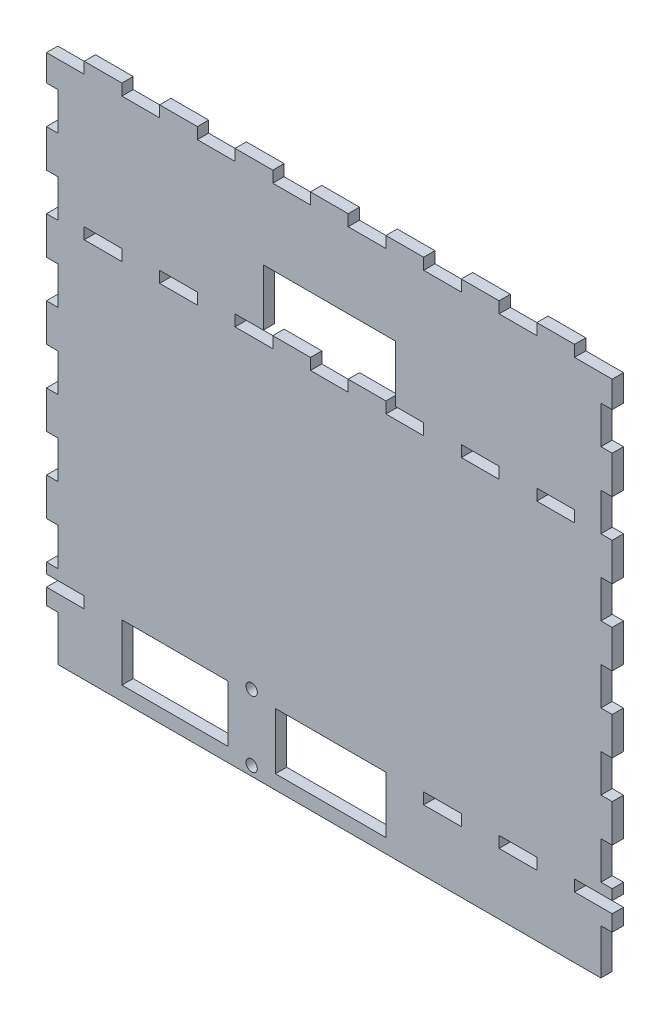
SolidWorks part; units mm, degrees
ref_plane "Alzado" through (0, 0, 0) normal (0, 0, 1) x (1, 0, 0)
ref_plane "Planta" through (0, 0, 0) normal (0, 1, 0) x (1, 0, 0)
ref_plane "Vista lateral" through (0, 0, 0) normal (1, 0, 0) x (0, 0, -1)
sketch "Croquis1" plane through (0, 0, 0) normal (0, 0, 1) x (1, 0, 0)
  line L0 (-45, 72.5) -> (-45, 69.5)
  line L1 (-72, -69.5) -> (72, -69.5)
  line L2 (-72, -69.5) -> (-72, 69.5)
  line L3 (-72, 69.5) -> (72, 69.5)
  line L4 (72, -69.5) -> (72, 69.5)
  line L5 (-72, -69.5) -> (72, 69.5) construction
  line L6 (-72, 69.5) -> (72, -69.5) construction
  line L7 (-65, 72.5) -> (-55, 72.5)
  line L8 (-65, 72.5) -> (-65, 69.5)
  line L9 (-65, 69.5) -> (-55, 69.5)
  line L10 (-55, 72.5) -> (-55, 69.5)
  line L11 (-45, 72.5) -> (-35, 72.5)
  line L12 (-35, 72.5) -> (-35, 69.5)
  line L13 (-45, 69.5) -> (-35, 69.5)
  line L14 (-25, 72.5) -> (-25, 69.5)
  line L15 (-25, 72.5) -> (-15, 72.5)
  line L16 (-15, 72.5) -> (-15, 69.5)
  line L17 (-25, 69.5) -> (-15, 69.5)
  line L18 (-5, 72.5) -> (-5, 69.5)
  line L19 (-5, 72.5) -> (5, 72.5)
  line L20 (5, 72.5) -> (5, 69.5)
  line L21 (-5, 69.5) -> (5, 69.5)
  line L22 (15, 72.5) -> (15, 69.5)
  line L23 (15, 72.5) -> (25, 72.5)
  line L24 (25, 72.5) -> (25, 69.5)
  line L25 (15, 69.5) -> (25, 69.5)
  line L26 (35, 72.5) -> (35, 69.5)
  line L27 (35, 72.5) -> (45, 72.5)
  line L28 (45, 72.5) -> (45, 69.5)
  line L29 (35, 69.5) -> (45, 69.5)
  line L30 (55, 72.5) -> (55, 69.5)
  line L31 (55, 72.5) -> (65, 72.5)
  line L32 (65, 72.5) -> (65, 69.5)
  line L33 (55, 69.5) -> (65, 69.5)
  line L58 (0, 0) -> (0, 41.2276) construction
  line L84 (-75, -50.25) -> (-65, -50.25)
  line L85 (-75, -50.25) -> (-75, -53.25)
  line L86 (-75, -53.25) -> (-65, -53.25)
  line L87 (-65, -50.25) -> (-65, -53.25)
  line L103 (25, -50.25) -> (25, -53.25)
  line L104 (25, -50.25) -> (35, -50.25)
  line L105 (35, -50.25) -> (35, -53.25)
  line L106 (25, -53.25) -> (35, -53.25)
  line L107 (45, -50.25) -> (45, -53.25)
  line L108 (45, -50.25) -> (55, -50.25)
  line L109 (55, -50.25) -> (55, -53.25)
  line L110 (45, -53.25) -> (55, -53.25)
  line L111 (65, -50.25) -> (65, -53.25)
  line L112 (65, -50.25) -> (75, -50.25)
  line L113 (75, -50.25) -> (75, -53.25)
  line L114 (65, -53.25) -> (75, -53.25)
  line L115 (-45, 34.5) -> (-45, 31.5)
  line L116 (-65, 34.5) -> (-55, 34.5)
  line L117 (-65, 34.5) -> (-65, 31.5)
  line L118 (-65, 31.5) -> (-55, 31.5)
  line L119 (-55, 34.5) -> (-55, 31.5)
  line L120 (-45, 34.5) -> (-35, 34.5)
  line L121 (-35, 34.5) -> (-35, 31.5)
  line L122 (-45, 31.5) -> (-35, 31.5)
  line L123 (-25, 34.5) -> (-25, 31.5)
  line L124 (-25, 34.5) -> (-15, 34.5)
  line L125 (-15, 34.5) -> (-15, 31.5)
  line L126 (-25, 31.5) -> (-15, 31.5)
  line L127 (-5, 34.5) -> (-5, 31.5)
  line L128 (-5, 34.5) -> (5, 34.5)
  line L129 (5, 34.5) -> (5, 31.5)
  line L130 (-5, 31.5) -> (5, 31.5)
  line L131 (15, 34.5) -> (15, 31.5)
  line L132 (15, 34.5) -> (25, 34.5)
  line L133 (25, 34.5) -> (25, 31.5)
  line L134 (15, 31.5) -> (25, 31.5)
  line L135 (35, 34.5) -> (35, 31.5)
  line L136 (35, 34.5) -> (45, 34.5)
  line L137 (45, 34.5) -> (45, 31.5)
  line L138 (35, 31.5) -> (45, 31.5)
  line L139 (55, 34.5) -> (55, 31.5)
  line L140 (55, 34.5) -> (65, 34.5)
  line L141 (65, 34.5) -> (65, 31.5)
  line L142 (55, 31.5) -> (65, 31.5)
  line L144 (-17.5, 49.5) -> (17.5, 49.5)
  line L145 (-17.5, 49.5) -> (-17.5, 34.5)
  line L146 (-17.5, 34.5) -> (17.5, 34.5)
  line L147 (17.5, 49.5) -> (17.5, 34.5)
  line L148 (-17.5, 49.5) -> (17.5, 34.5) construction
  line L149 (-17.5, 34.5) -> (17.5, 49.5) construction
  line L197 (-72, -27.5) -> (-72, -37.5)
  line L198 (-72, -47.5) -> (-75, -47.5)
  line L199 (-72, -47.5) -> (-72, -57.5)
  line L200 (-72, -57.5) -> (-75, -57.5)
  line L201 (-75, -47.5) -> (-75, -57.5)
  line L202 (-72, -27.5) -> (-75, -27.5)
  line L203 (-75, -27.5) -> (-75, -37.5)
  line L204 (-72, -37.5) -> (-75, -37.5)
  line L205 (-72, -7.5) -> (-72, -17.5)
  line L206 (-72, -7.5) -> (-75, -7.5)
  line L207 (-75, -7.5) -> (-75, -17.5)
  line L208 (-72, -17.5) -> (-75, -17.5)
  line L209 (-72, 12.5) -> (-72, 2.5)
  line L210 (-72, 12.5) -> (-75, 12.5)
  line L211 (-75, 12.5) -> (-75, 2.5)
  line L212 (-72, 2.5) -> (-75, 2.5)
  line L213 (-72, 32.5) -> (-72, 22.5)
  line L214 (-72, 32.5) -> (-75, 32.5)
  line L215 (-75, 32.5) -> (-75, 22.5)
  line L216 (-72, 22.5) -> (-75, 22.5)
  line L217 (-72, 52.5) -> (-72, 42.5)
  line L218 (-72, 52.5) -> (-75, 52.5)
  line L219 (-75, 52.5) -> (-75, 42.5)
  line L220 (-72, 42.5) -> (-75, 42.5)
  line L221 (72, -57.5) -> (75, -57.5)
  line L222 (-72, 69.5) -> (-75, 69.5)
  line L223 (-72, 69.5) -> (-72, 62.5)
  line L224 (-72, 62.5) -> (-75, 62.5)
  line L225 (-75, 69.5) -> (-75, 62.5)
  line L226 (75, -47.5) -> (75, -57.5)
  line L227 (72, -47.5) -> (75, -47.5)
  line L228 (72, -47.5) -> (72, -57.5)
  line L229 (72, -27.5) -> (75, -27.5)
  line L230 (75, -27.5) -> (75, -37.5)
  line L231 (72, -37.5) -> (75, -37.5)
  line L232 (72, -27.5) -> (72, -37.5)
  line L233 (72, -7.5) -> (75, -7.5)
  line L234 (75, -7.5) -> (75, -17.5)
  line L235 (72, -17.5) -> (75, -17.5)
  line L236 (72, -7.5) -> (72, -17.5)
  line L237 (72, 12.5) -> (75, 12.5)
  line L238 (75, 12.5) -> (75, 2.5)
  line L239 (72, 2.5) -> (75, 2.5)
  line L240 (72, 12.5) -> (72, 2.5)
  line L241 (72, 32.5) -> (75, 32.5)
  line L242 (75, 32.5) -> (75, 22.5)
  line L243 (72, 22.5) -> (75, 22.5)
  line L244 (72, 32.5) -> (72, 22.5)
  line L245 (72, 52.5) -> (75, 52.5)
  line L246 (75, 52.5) -> (75, 42.5)
  line L247 (72, 42.5) -> (75, 42.5)
  line L248 (72, 52.5) -> (72, 42.5)
  line L249 (72, 62.5) -> (75, 62.5)
  line L250 (75, 69.5) -> (75, 62.5)
  line L251 (72, 69.5) -> (75, 69.5)
  line L252 (72, 69.5) -> (72, 62.5)
  line L253 (-15, -50.25) -> (-15, -53.25) [skipped]
  line L254 (-15, -53.25) -> (-5, -53.25) [skipped]
  line L255 (-5, -50.25) -> (-5, -53.25) [skipped]
  line L256 (-15, -50.25) -> (-5, -50.25) [skipped]
  line L257 (5, -50.25) -> (5, -53.25) [skipped]
  line L258 (5, -53.25) -> (15, -53.25) [skipped]
  line L259 (15, -50.25) -> (15, -53.25) [skipped]
  line L260 (5, -50.25) -> (15, -50.25) [skipped]
  line L261 (-35, -50.25) -> (-35, -53.25) [skipped]
  line L262 (-35, -53.25) -> (-25, -53.25) [skipped]
  line L263 (-25, -50.25) -> (-25, -53.25) [skipped]
  line L264 (-35, -50.25) -> (-25, -50.25) [skipped]
  line L265 (-55, -53.25) -> (-45, -53.25) [skipped]
  line L266 (-45, -50.25) -> (-45, -53.25) [skipped]
  line L267 (-55, -50.25) -> (-45, -50.25) [skipped]
  line L268 (-55, -50.25) -> (-55, -53.25) [skipped]
  line L274 (-14.3, -65.75) -> (15, -65.75)
  line L275 (-14.3, -65.75) -> (-14.3, -50.75)
  line L276 (-14.3, -50.75) -> (15, -50.75)
  line L277 (15, -65.75) -> (15, -50.75)
  line L278 (-14.3, -65.75) -> (15, -50.75) construction
  line L279 (-14.3, -50.75) -> (15, -65.75) construction
  line L280 (-55, -65.75) -> (-26.9, -65.75)
  line L281 (-55, -65.75) -> (-55, -50.75)
  line L282 (-55, -50.75) -> (-26.9, -50.75)
  line L283 (-26.9, -65.75) -> (-26.9, -50.75)
  line L284 (-55, -65.75) -> (-26.9, -50.75) construction
  line L285 (-55, -50.75) -> (-26.9, -65.75) construction
  circle A1 centre (-20.6, -49.5) radius 1.5
  circle A2 centre (-20.6, -67) radius 1.5
  point P0 (0, 0)
  point P39 (-65, -51.75)
  point P89 (65, -51.75)
  point P90 (55, -51.75)
  point P91 (0, 0)
  point P97 (0.35, -58.25)
  point P103 (-40.95, -58.25)
  point P120 (0, 42)
  dimension "D29" = 8.75
  dimension "D31" = 3
  dimension "D1" = 144
  dimension "D2" = 139
  dimension "D3" = 10
  dimension "D4" = 3
  dimension "D5" = 7
  dimension "D7" = 10
  dimension "D8" = 10
  dimension "D9" = 3
  dimension "D10" = 12
  dimension "D12" = 10
  dimension "D13" = 10
  dimension "D14" = 3
  dimension "D16" = 16.25
  dimension "D17" = 10
  dimension "D18" = 10
  dimension "D19" = 3
  dimension "D20" = 7
  dimension "D22" = 10
  dimension "D23" = 35
  dimension "D24" = 15
  dimension "D25" = 35
  dimension "D26" = 7
  dimension "D27" = 3
  dimension "D28" = 7
  dimension "D30" = 2.75
  dimension "D32" = 5
  dimension "D33" = 10
  dimension "D34" = 17.5
  dimension "D35" = 15
  dimension "D36" = 6.3
  dimension "D38" = 6.3
  dimension "D39" = 17
  dimension "D40" = 70
  dimension "D41" = 92.6
  dimension "D42" = 20
  dimension "D6" = 7
  dimension "D15" = 8
  dimension "D21" = 7
  dimension "D11" = 6
extrude "Saliente-Extruir3" add sketch "Croquis1" along normal blind 3 contours L114 L111 L112 L4 L3 L2 L84 L87 L86 L1 | L208 L2 L206 L207 | L212 L2 L210 L211 | L204 L2 L202 L203 | L198 L201 L84 L2 | L86 L201 L200 L2 | L220 L2 L218 L219 | L10 L7 L8 L3 | L12 L11 L0 L3 | L16 L15 L14 L3 | L20 L19 L18 L3 | L24 L23 L22 L3 | L28 L27 L26 L3 | L32 L31 L30 L3 | L251 L4 L249 L250 | L4 L247 L246 L245 | L4 L243 L242 L241 | L4 L239 L238 L237 | L4 L235 L234 L233 | L4 L231 L230 L229 | L227 L4 L112 L226 | L226 L114 L4 L221 | L215 L216 L213 L214 | L223 L222 L225 L224
ref_plane "Plano1" through (-75, -17.5, 0) normal (0, -1, 0) x (-1, 0, 0)
